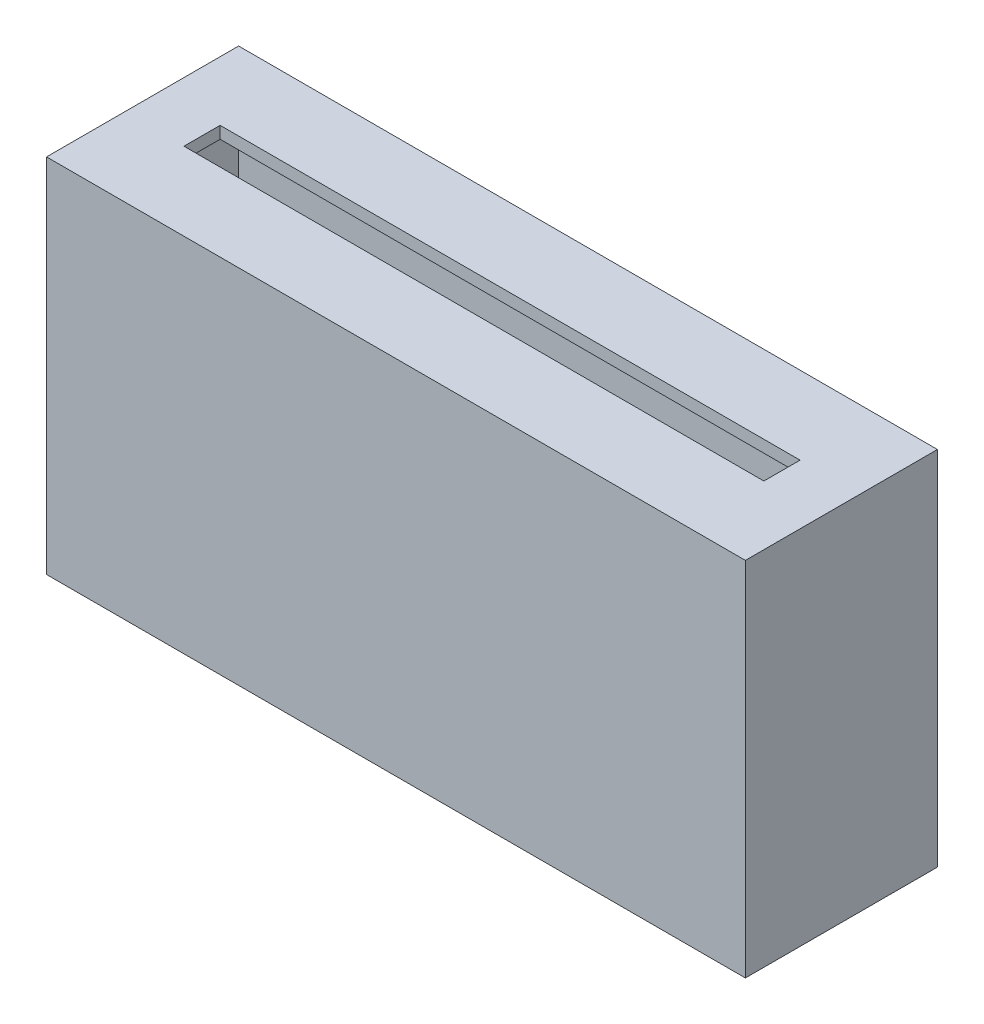
SolidWorks part; units mm, degrees
ref_plane "Front Plane" through (0, 0, 0) normal (0, 0, 1) x (1, 0, 0)
ref_plane "Top Plane" through (0, 0, 0) normal (0, 1, 0) x (1, 0, 0)
ref_plane "Right Plane" through (0, 0, 0) normal (1, 0, 0) x (0, 0, -1)
sketch "Sketch1" plane through (0, 0, 0) normal (0, 1, 0) x (1, 0, 0)
  line L1 (-73.6143, -20.2318) -> (73.6143, -20.2318)
  line L2 (-73.6143, -20.2318) -> (-73.6143, 20.2318)
  line L3 (-73.6143, 20.2318) -> (73.6143, 20.2318)
  line L4 (73.6143, -20.2318) -> (73.6143, 20.2318)
  line L5 (-73.6143, -20.2318) -> (73.6143, 20.2318) construction
  line L6 (-73.6143, 20.2318) -> (73.6143, -20.2318) construction
  point P0 (0, 0)
extrude "Boss-Extrude1" add sketch "Sketch1" along normal blind 76.2
shell "Shell1" thickness 2.54
sketch "Sketch2" plane through (0, 76.2, 0) normal (0, 1, 0) x (1, 0, 0)
  line L1 (-61.087, -3.81) -> (61.087, -3.81)
  line L2 (-61.087, -3.81) -> (-61.087, 3.81)
  line L3 (-61.087, 3.81) -> (61.087, 3.81)
  line L4 (61.087, -3.81) -> (61.087, 3.81)
  line L5 (-61.087, -3.81) -> (61.087, 3.81) construction
  line L6 (-61.087, 3.81) -> (61.087, -3.81) construction
  point P0 (0, 0)
  dimension "D1" = 122.174
  dimension "D2" = 7.62
extrude "Cut-Extrude1" cut sketch "Sketch2" against normal blind 2.54
